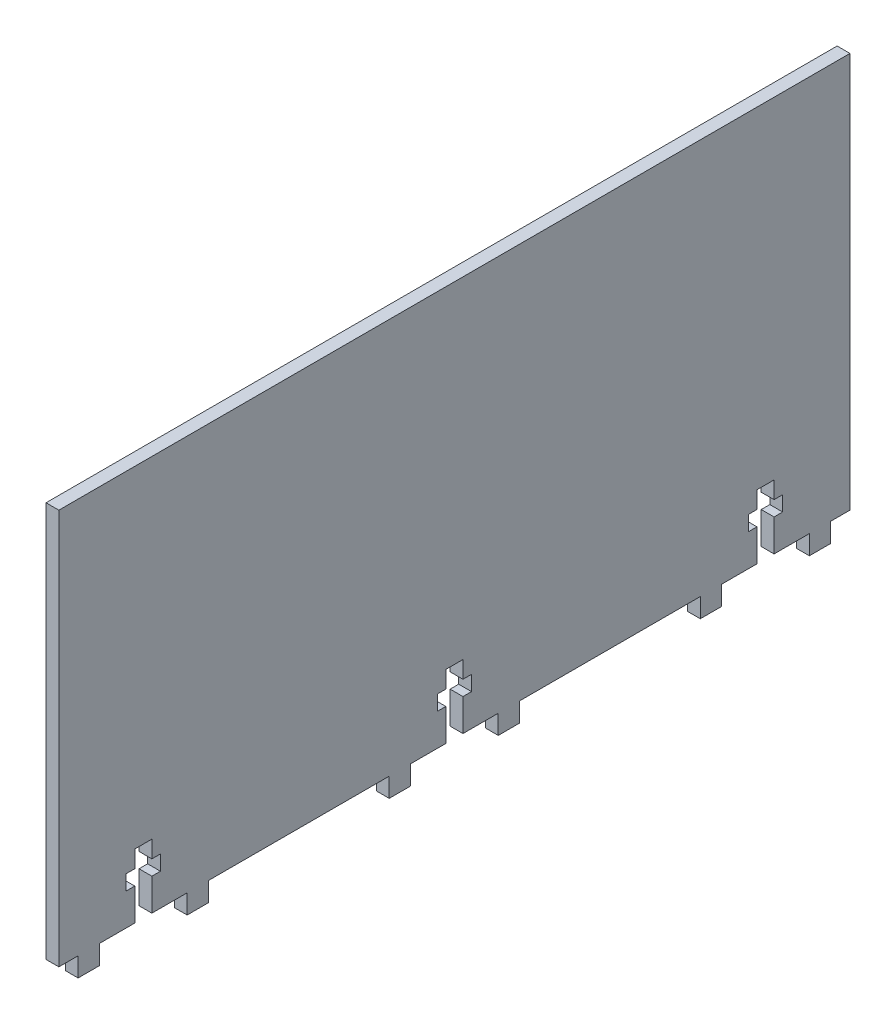
SolidWorks part; units mm, degrees
ref_plane "Front Plane" through (0, 0, 0) normal (0, 0, 1) x (1, 0, 0)
ref_plane "Top Plane" through (0, 0, 0) normal (0, 1, 0) x (1, 0, 0)
ref_plane "Right Plane" through (0, 0, 0) normal (1, 0, 0) x (0, 0, -1)
sketch "Sketch1" plane through (0, 0, 0) normal (1, 0, 0) x (0, 0, -1)
  line L0 (-185, -92.5) -> (185, 92.5) construction
  line L1 (-185, 92.5) -> (185, 92.5)
  line L2 (-185, 92.5) -> (-185, -92.5)
  line L3 (-185, -92.5) -> (-176, -92.5)
  line L4 (185, 92.5) -> (185, -92.5)
  line L5 (0, 92.5) -> (0, -92.5) construction
  line L6 (149.5, -92.5) -> (149.5, -77.5)
  line L7 (149.5, -77.5) -> (153.5, -77.5)
  line L8 (153.5, -77.5) -> (153.5, -70.5)
  line L9 (153.5, -70.5) -> (149.5, -70.5)
  line L10 (149.5, -70.5) -> (149.5, -62.5)
  line L11 (149.5, -62.5) -> (141.5, -62.5)
  line L12 (141.5, -62.5) -> (141.5, -70.5)
  line L13 (141.5, -70.5) -> (137.5, -70.5)
  line L14 (137.5, -70.5) -> (137.5, -77.5)
  line L15 (137.5, -77.5) -> (141.5, -77.5)
  line L16 (141.5, -77.5) -> (141.5, -92.5)
  line L17 (166, -92.5) -> (166, -101.5)
  line L18 (166, -101.5) -> (176, -101.5)
  line L19 (176, -101.5) -> (176, -92.5)
  line L20 (115, -92.5) -> (115, -101.5)
  line L21 (115, -101.5) -> (125, -101.5)
  line L22 (125, -101.5) -> (125, -92.5)
  line L23 (30.5, -92.5) -> (30.5, -101.5)
  line L24 (30.5, -101.5) -> (20.5, -101.5)
  line L25 (20.5, -101.5) -> (20.5, -92.5)
  line L26 (-20.5, -92.5) -> (-20.5, -101.5)
  line L27 (-20.5, -101.5) -> (-30.5, -101.5)
  line L28 (-30.5, -101.5) -> (-30.5, -92.5)
  line L29 (-115, -92.5) -> (-115, -101.5)
  line L30 (-115, -101.5) -> (-125, -101.5)
  line L31 (-125, -101.5) -> (-125, -92.5)
  line L32 (-176, -92.5) -> (-176, -101.5)
  line L33 (-176, -101.5) -> (-166, -101.5)
  line L34 (-166, -101.5) -> (-166, -92.5)
  line L35 (166, -97) -> (125, -97) construction
  line L36 (115, -97) -> (30.5, -97) construction
  line L37 (20.5, -97) -> (-20.5, -97) construction
  line L38 (-30.5, -97) -> (-115, -97) construction
  line L39 (-125, -97) -> (-166, -97) construction
  line L40 (-166, -92.5) -> (-125, -92.5)
  line L41 (-115, -92.5) -> (-30.5, -92.5)
  line L42 (-20.5, -92.5) -> (20.5, -92.5)
  line L43 (30.5, -92.5) -> (115, -92.5)
  line L44 (125, -92.5) -> (166, -92.5)
  line L45 (145.5, -62.5) -> (145.5, -92.5) construction
  line L46 (176, -92.5) -> (185, -92.5)
  line L47 (72.75, -92.5) -> (72.75, 92.5) construction
  line L48 (-4, -92.5) -> (-4, -77.5)
  line L49 (-4, -77.5) -> (-8, -77.5)
  line L50 (-8, -77.5) -> (-8, -70.5)
  line L51 (-8, -70.5) -> (-4, -70.5)
  line L52 (-4, -70.5) -> (-4, -62.5)
  line L53 (-4, -62.5) -> (4, -62.5)
  line L54 (4, -62.5) -> (4, -70.5)
  line L55 (4, -70.5) -> (8, -70.5)
  line L56 (8, -70.5) -> (8, -77.5)
  line L57 (8, -77.5) -> (4, -77.5)
  line L58 (4, -77.5) -> (4, -92.5)
  line L59 (-149.5, -92.5) -> (-149.5, -77.5)
  line L60 (-149.5, -77.5) -> (-153.5, -77.5)
  line L61 (-153.5, -77.5) -> (-153.5, -70.5)
  line L62 (-153.5, -70.5) -> (-149.5, -70.5)
  line L63 (-149.5, -70.5) -> (-149.5, -62.5)
  line L64 (-149.5, -62.5) -> (-141.5, -62.5)
  line L65 (-141.5, -62.5) -> (-141.5, -70.5)
  line L66 (-141.5, -70.5) -> (-137.5, -70.5)
  line L67 (-137.5, -70.5) -> (-137.5, -77.5)
  line L68 (-141.5, -77.5) -> (-141.5, -92.5)
  line L69 (-137.5, -77.5) -> (-141.5, -77.5)
  point P72 (0, 0)
  dimension "D1" = 370
  dimension "D2" = 185
  dimension "D3" = 8
  dimension "D4" = 8
  dimension "D5" = 7
  dimension "D6" = 15
  dimension "D7" = 4
  dimension "D8" = 10
  dimension "D9" = 9
  dimension "D10" = 9
  dimension "D11" = 84.5
  dimension "D12" = 41
extrude "Boss-Extrude1" add sketch "Sketch1" along normal mid plane 6 contours L67 L69 L68 L40 L31 L30 L29 L41 L28 L27 L26 L42 L48 L49 L50 L51 L52 L53 L54 L55 L56 L57 L58 L25 L24 L23 L43 L20 L21 L22 L44 L16 L15 L14 L13 L12 L11 L10 L9 L8 L7 L6 L17 L18 L19 L46 L4 L1 L2
